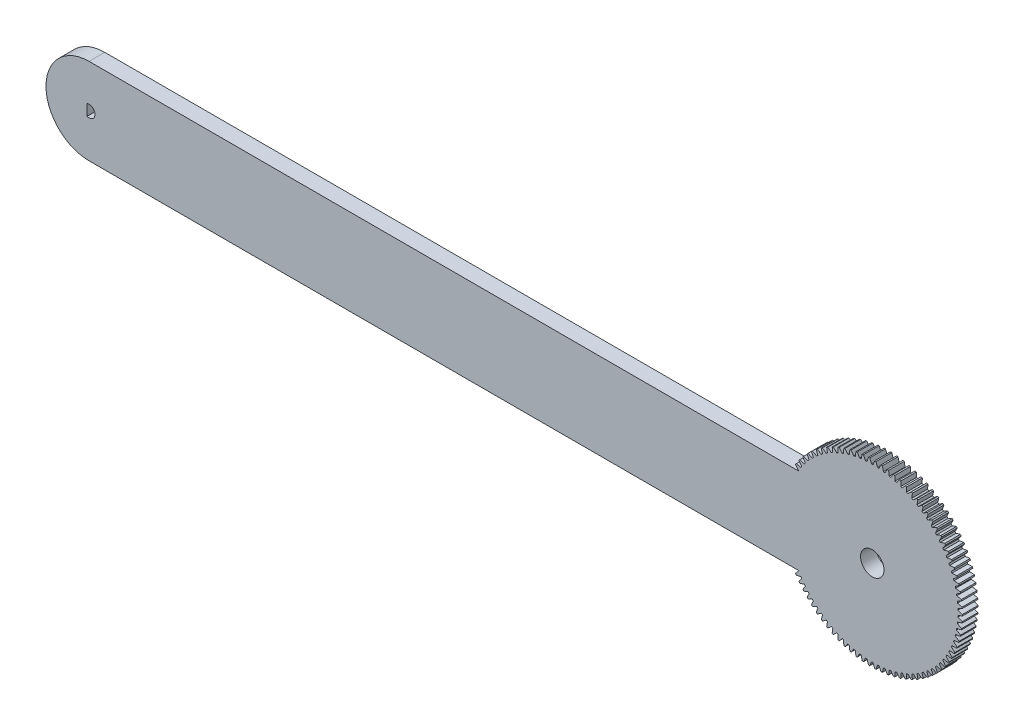
SolidWorks part; units mm, degrees
material "Alumina"
ref_plane "Plane1" through (0, 0, 0) normal (0, 0, 1) x (1, 0, 0)
ref_plane "Plane2" through (0, 0, 0) normal (0, 1, 0) x (1, 0, 0)
ref_plane "Plane3" through (0, 0, 0) normal (1, 0, 0) x (0, 0, -1)
sketch "HoldingSke" plane through (0, 0, 0) normal (0, 1, 0) x (1, 0, 0)
  line L0 (0, 0) -> (0, -2)
  line L1 (-15, 0) -> (100, 0) construction
  line L2 (0, 0) -> (-2.1039, 2.3779)
  line L3 (0, 0) -> (-11.863, 4.5341)
  line L4 (0, 0) -> (0, 8.636)
  line L5 (0, 0) -> (-46.8476, -17.4728)
  line L6 (0, 0) -> (-3.3159, -2.2372)
  line L7 (-2.1039, 2.3779) -> (8.6586, 51.2059)
  line L8 (-76.2, 54.61) -> (-74.4, 54.61)
  line L9 (-71.009, 38.7566) -> (-53.1078, 45.2721)
  line L10 (-76.2, 71.12) -> (104.1128, 71.12)
  line L11 (0, 0) -> (-4, 0)
  line L12 (-76.2, 101.6) -> (-76.181, 101.6)
  line L13 (24.9733, 27.94) -> (52.9518, 28.4284)
  line L14 (24.9733, 27.94) -> (24.9743, 27.94)
  line L15 (24.9733, 27.94) -> (100.4006, 29.5858)
  line L16 (-63.627, -0.5) -> (-12.827, -0.5)
  circle A0 centre (0, 0) radius 5
  circle A1 centre (0, 0) radius 21.874
  circle A2 centre (0, 0) radius 37.5
  circle A3 centre (0, 0) radius 5
  dimension "MHD" = 43.748
  dimension "Hub_dia" = 75
  dimension "Bore" = 10
  dimension "MBD" = 10
  dimension "Num_teeth" = 90
  dimension "Pitch" = 2
  dimension "Overall_len" = 50
  dimension "Show_teeth" = 90
  dimension "Thickness" = 4
  dimension "OAL" = 50.0001
  dimension "T_dim" = 1.8
  dimension "Ap" = 20
  dimension "H" = 19.05
  dimension "Pitch_radius" = 180.3128
  dimension "Width" = 4
  dimension "Backlash" = 0.019
  dimension "Addendum_fac" = 1
  dimension "Dedendum_fac" = 1.25
  dimension "Clearance_fac" = 0.25
  dimension "Dedendum_add" = 0.001
  dimension "Module" = 0.5
sketch "BasProSke" plane through (0, 0, 0) normal (0, 1, 0) x (1, 0, 0)
  line L0 (-10, 0) -> (60, 0) construction
  line L1 (0, 0) -> (0, 23)
  line L2 (0, 0) -> (4, 0)
  line L3 (4, 0) -> (4, 23)
  line L4 (4, 23) -> (0, 23)
  dimension "Thickness" = 4
  dimension "Diameter" = 46
revolve "Base-Revolve" add sketch "BasProSke" angle 360 about L0
sketch "TooCutSke" plane through (0, 0, 0) normal (1, 0, 0) x (0, 0, -1)
  line L1 (0, 0) -> (0, 107) construction
  line L2 (0, 0) -> (-0.4259, 22.496) construction
  line L3 (0, 0) -> (-1.5703, 44.9668) construction
  line L4 (-0.4259, 22.496) -> (-0.7851, 22.4834) construction
  arc A0 (0.2085, 21.873) -> (-0.2085, 21.873) centre (0, 0) ccw
  arc A1 (0.6483, 23.0163) -> (-0.6483, 23.0163) centre (0, 0) ccw
  circle A2 centre (0, 0) radius 22.5 construction
  circle A3 centre (0, 0) radius 21.1431 construction
  arc A4 (-0.2085, 21.873) -> (-0.6483, 23.0163) centre (-8.8088, 19.2207) ccw
  arc A5 (0.6483, 23.0163) -> (0.2085, 21.873) centre (8.8088, 19.2207) ccw
  dimension "Root_dia" = 43.748
  dimension "Overcut_dia" = 46.0508
  dimension "Pitch_dia" = 45
  dimension "Base_dia" = 42.2862
  dimension "Flank_rad" = 9
  dimension "Half_ang" = 2
  dimension "Half_CT" = 0.3594
extrude "ToothCut" cut sketch "TooCutSke" along normal through all
fillet "Breaks" [suppressed] radius 0.01
fillet "RootFillets" [suppressed] radius 0.126
pattern_circular "TeethCuts" count 90 every 4 about axis through (-10, 0, 0) along (1, 0, 0) of "ToothCut", "RootFillets", "Breaks"
sketch "HubNeaOneSke" plane through (0, 0, 0) normal (-1, 0, 0) x (0, 0, 1)
  circle A0 centre (0, 0) radius 21.874
  dimension "Diameter" = 43.748
extrude "HubNearOne" [suppressed] add sketch "HubNeaOneSke" along normal blind 46.0001
sketch "HubNeaBotSke" plane through (0, 0, 0) normal (-1, 0, 0) x (0, 0, 1)
  circle A0 centre (0, 0) radius 21.874
  dimension "Diameter" = 43.748
extrude "HubNearBoth" [suppressed] add sketch "HubNeaBotSke" along normal blind 23
ref_plane "FarPln" through (4, 0, 0) normal (1, 0, 0) x (0, 0, -1)
sketch "HubFarSke" plane through (4, 0, 0) normal (1, 0, 0) x (0, 0, -1)
  circle A0 centre (0, 0) radius 21.874
  dimension "Diameter" = 43.748
extrude "HubFar" [suppressed] add sketch "HubFarSke" along normal blind 23
sketch "BorSke" plane through (0, 0, 0) normal (1, 0, 0) x (0, 0, -1)
  circle A0 centre (0, 0) radius 5
  dimension "Diameter" = 10
extrude "Bore" cut sketch "BorSke" along normal mid plane 100.0001
sketch "KeySke" plane through (0, 0, 0) normal (1, 0, 0) x (0, 0, -1)
  line L0 (-2, 0) -> (-2, 6.8)
  line L1 (-2, 6.8) -> (2, 6.8)
  line L2 (2, 6.8) -> (2, 0)
  line L3 (0, 0) -> (0, 34) construction
  line L4 (-2, 0) -> (2, 0)
  dimension "Width" = 4
  dimension "Offset" = 6.8
extrude "Keyway" [suppressed] cut sketch "KeySke" along normal mid plane 100.0001
pattern_circular "Keyway2" [suppressed] count 2 every 90 about axis through (-10, 0, 0) along (1, 0, 0)
sketch "Sketch1" plane through (0, 0, 0) normal (1, 0, 0) x (0, 0, -1)
  line L0 (0, 0) -> (-200, 0) construction
  line L1 (0, -11) -> (-200, -11)
  line L2 (0, 11) -> (-200, 11)
  arc A0 (0, -11) -> (0, 11) centre (0, 0) ccw
  arc A1 (-200, 11) -> (-200, -11) centre (-200, 0) ccw
  point P3 (-100, 0)
extrude "Boss-Extrude1" add sketch "Sketch1" along normal blind 4 contours L2 A1 L1 A0
sketch "Sketch3" plane through (0, 0, 0) normal (1, 0, 0) x (0, 0, -1)
  line L0 (-200, 11) -> (-200, -11) construction
  line L1 (-18.9069, 11) -> (-200, 11) construction
  line L2 (-198.5, 0) -> (-200.5, 0) construction
  line L3 (-200.5, 1.4142) -> (-200.5, -1.4142)
  arc A1 (-200, 11) -> (-200, -11) centre (-200, 0) ccw construction
  circle A2 centre (-200, 0) radius 1.5
  point P17 (0, 0)
extrude "Cut-Extrude2" cut sketch "Sketch3" along normal through all contours L3 A2
sketch "Sketch4" plane through (0, 0, 0) normal (1, 0, 0) x (0, 0, -1)
  circle A0 centre (0, 0) radius 3
extrude "Cut-Extrude4" cut sketch "Sketch4" along normal through all
move or copy body "Body-Move/Copy1" bodies to move or copy 106 copy no rotation origin (2, 0, 94) rotation axis (0, 1, 0) rotation angle 90
move or copy body "Body-Move/Copy2" bodies to move or copy 107 copy no rotation origin (2, 0, 0) rotation axis (0, 0, 1) rotation angle 180
equation "' \"Module@HoldingSke\" = 6.35"
equation "' \"Num_teeth@HoldingSke\" = 12"
equation "' \"Ap@HoldingSke\" =  20"
equation "' \"Ap@HoldingSke\" = 20"
equation "' \"Width@HoldingSke\" = 0.5 * 25.4"
equation "' \"Hub_dia@HoldingSke\"= 1 * 25.4"
equation "' \"Hub_dia@HoldingSke\" = 1 * 25.4"
equation "' \"Overall_len@HoldingSke\" = 1.0 * 25.4"
equation "' \"Bore@HoldingSke\" = 0.75 * 25.4"
equation "' \"T_dim@HoldingSke\" = 0.1 * 25.4"
equation "' \"Width@KeySke\" = 0.25 * 25.4"
equation "' \"Show_teeth@HoldingSke\" = 13"
equation "' \"Backlash@HoldingSke\" = 0.009 * 25.4"
equation "' \"Addendum_fac@HoldingSke\" = 1.0"
equation "' \"Dedendum_fac@HoldingSke\" = 1.25"
equation "' \"Dedendum_add@HoldingSke\" = 0.00005 * 25.4"
equation "' \"Clearance_fac@HoldingSke\" = 0.25"
equation "\"Pitch@HoldingSke\" = 1 / \"Module@HoldingSke\""
equation "\"Overcut_dia@TooCutSke\" = (\"Num_teeth@HoldingSke\" + 2 * \"Addendum_fac@HoldingSke\") / \"Pitch@HoldingSke\" + 0.002 * 25.4"
equation "\"Pitch_dia@TooCutSke\" = \"Num_teeth@HoldingSke\" / \"Pitch@HoldingSke\""
equation "\"Base_dia@TooCutSke\" = \"Num_teeth@HoldingSke\" / \"Pitch@HoldingSke\" * cos((\"Ap@HoldingSke\"  * 3.14159265 / 180))"
equation "\"Root_dia@TooCutSke\" = (\"Num_teeth@HoldingSke\" + 2) / \"Pitch@HoldingSke\" - 2 * (\"Addendum_fac@HoldingSke\" + \"Dedendum_fac@HoldingSke\") / \"Pitch@HoldingSke\" - \"Dedendum_add@HoldingSke\" * 2"
equation "\"Half_ang@TooCutSke\" = 180 / \"Num_teeth@HoldingSke\""
equation "\"Half_CT@TooCutSke\" = \"Num_teeth@HoldingSke\" / \"Pitch@HoldingSke\" * sin((3.14159265 / 2 / \"Num_teeth@HoldingSke\")) / 2 - 7 * \"Backlash@HoldingSke\" / 4"
equation "\"Flank_rad@TooCutSke\" = \"Num_teeth@HoldingSke\" / \"Pitch@HoldingSke\" / 5"
equation "\"Radius@RootFillets\" = \"Clearance_fac@HoldingSke\" / \"Pitch@HoldingSke\" + \"Dedendum_add@HoldingSke\""
equation "\"Break_rad@Breaks\" = 0.02 / \"Pitch@HoldingSke\""
equation "\"Thickness@HoldingSke\" = \"Width@HoldingSke\""
equation "\"OAL@HoldingSke\" = \"Thickness@HoldingSke\""
equation "\"MHD@HoldingSke\" = (\"Num_teeth@HoldingSke\" + 2) / \"Pitch@HoldingSke\" - 2 * (\"Addendum_fac@HoldingSke\" + \"Dedendum_fac@HoldingSke\")  / \"Pitch@HoldingSke\" - \"Dedendum_add@HoldingSke\" * 2"
equation "\"MBD@HoldingSke\" = (\"Num_teeth@HoldingSke\" + 2) / \"Pitch@HoldingSke\" - 2 * (\"Addendum_fac@HoldingSke\" + \"Dedendum_fac@HoldingSke\")  / \"Pitch@HoldingSke\" - \"Dedendum_add@HoldingSke\" * 2 - 0.002 * 25.4"
equation "\"MHD@HoldingSke\" = ((sgn( \"MHD@HoldingSke\" - \"Hub_dia@HoldingSke\" )-1)*( \"MHD@HoldingSke\" - \"Hub_dia@HoldingSke\" ))/-2+ \"Hub_dia@HoldingSke\""
equation "\"MBD@HoldingSke\" = ((sgn( \"MBD@HoldingSke\" - \"Bore@HoldingSke\" )-1)*( \"MBD@HoldingSke\" - \"Bore@HoldingSke\" ))/-2+ \"Bore@HoldingSke\""
equation "\"OAL@HoldingSke\" = ((sgn( \"OAL@HoldingSke\" - \"Overall_len@HoldingSke\" )+1)*( \"OAL@HoldingSke\" - \"Overall_len@HoldingSke\" ))/2 + \"Overall_len@HoldingSke\" + 0.000002 * 25.4"
equation "\"Num_teeth@TeethCuts\" = int( \"Show_teeth@HoldingSke\" ) + 1"
equation "\"Num_teeth@TeethCuts\" = ((sgn( \"Num_teeth@TeethCuts\" - \"Num_teeth@HoldingSke\" )-1)*( \"Num_teeth@TeethCuts\" - \"Num_teeth@HoldingSke\" ))/-2+ \"Num_teeth@HoldingSke\""
equation "\"Num_teeth@TeethCuts\" = ((sgn( \"Num_teeth@TeethCuts\" - 2.0)+1)*( \"Num_teeth@TeethCuts\" - 2.0))/2 +2.0"
equation "\"Angle@TeethCuts\" = 360.0 / \"Num_teeth@HoldingSke\""
equation "\"Diameter@BasProSke\" = (\"Num_teeth@HoldingSke\" + 2 * \"Addendum_fac@HoldingSke\") / \"Pitch@HoldingSke\""
equation "\"Thickness@BasProSke\"  = \"Thickness@HoldingSke\""
equation "' \"Fillet_rad@BasProSke\" =  \"Thickness@HoldingSke\" * 0.05"
equation "' \"Fillet_rad@BasProSke\" = \"Thickness@HoldingSke\" * 0.05"
equation "\"MHD@HoldingSke\" = ((sgn( \"MHD@HoldingSke\" - \"Root_dia@TooCutSke\" )-1)*( \"MHD@HoldingSke\" - \"Root_dia@TooCutSke\" ))/-2+ \"Root_dia@TooCutSke\""
equation "\"Diameter@HubNeaOneSke\" = \"MHD@HoldingSke\""
equation "\"Length@HubNearOne\" = \"OAL@HoldingSke\" - \"Thickness@BasProSke\""
equation "\"Diameter@HubNeaBotSke\" = \"MHD@HoldingSke\""
equation "\"Length@HubNearBoth\" = ( \"OAL@HoldingSke\" - \"Thickness@BasProSke\" ) / 2.0"
equation "\"Thickness@FarPln\" = \"Thickness@BasProSke\""
equation "\"Diameter@HubFarSke\" = \"MHD@HoldingSke\""
equation "\"Length@HubFar\" = ( \"OAL@HoldingSke\" - \"Thickness@BasProSke\" ) / 2.0"
equation "\"Diameter@BorSke\" = \"MBD@HoldingSke\""
equation "\"D1@Bore\" = \"OAL@HoldingSke\" * 2.0"
equation "\"D1@Keyway\" = \"OAL@HoldingSke\" * 2.0"
equation "\"Offset@KeySke\" = \"T_dim@HoldingSke\" + \"MBD@HoldingSke\" / 2.0"
